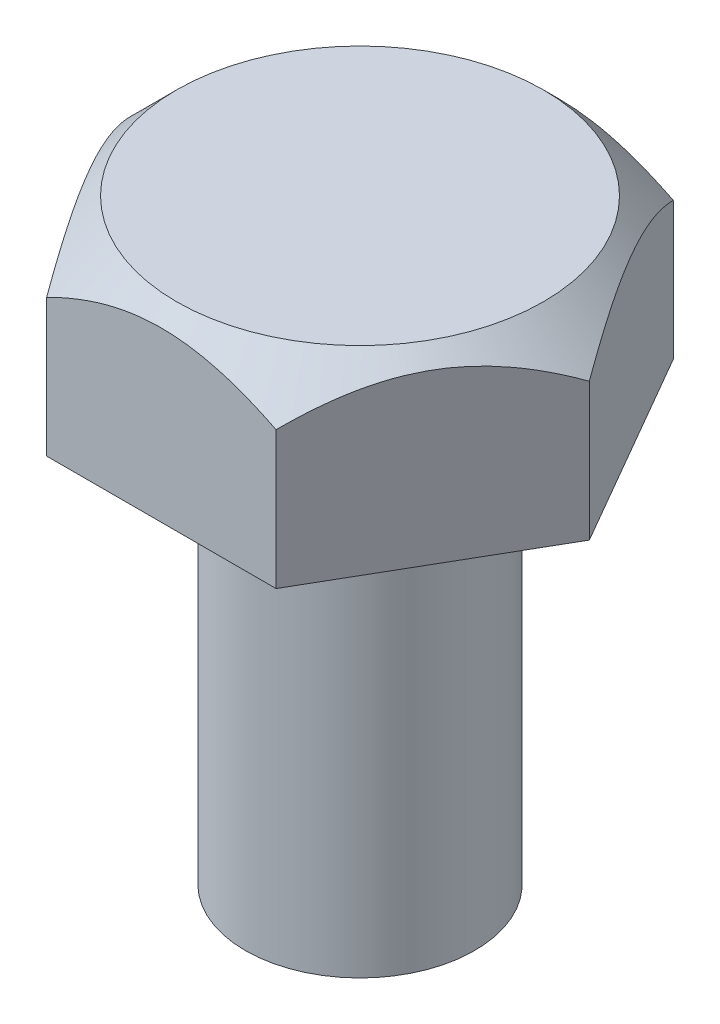
SolidWorks part; units mm, degrees
ref_plane "Front Plane" through (0, 0, 0) normal (0, 0, 1) x (1, 0, 0)
ref_plane "Top Plane" through (0, 0, 0) normal (0, 1, 0) x (1, 0, 0)
ref_plane "Right Plane" through (0, 0, 0) normal (1, 0, 0) x (0, 0, -1)
sketch "Sketch1" plane through (0, 0, 0) normal (0, 1, 0) x (1, 0, 0)
  circle A0 centre (0, 0) radius 2.5
  dimension "D1" = 5
extrude "Boss-Extrude1" add sketch "Sketch1" along normal blind 9
sketch "Sketch2" plane through (0, 9, 0) normal (0, 1, 0) x (1, 0, 0)
  line L1 (-2.5, -4.3301) -> (2.5, -4.3301)
  line L2 (2.5, -4.3301) -> (5, 0)
  line L3 (5, 0) -> (2.5, 4.3301)
  line L4 (2.5, 4.3301) -> (-2.5, 4.3301)
  line L5 (-2.5, 4.3301) -> (-5, 0)
  line L6 (-5, 0) -> (-2.5, -4.3301)
  circle A0 centre (0, 0) radius 4.3301 construction
  dimension "D1" = 10
extrude "Boss-Extrude2" add sketch "Sketch2" along normal blind 4
sketch "Sketch3" plane through (0, 0, 0) normal (0, 0, 1) x (1, 0, 0)
  line L0 (4, 13) -> (5, 12)
  line L1 (2.5, 13) -> (5, 13) construction
  line L2 (5, 13) -> (5, 9) construction
  line L3 (5, 12) -> (5, 13)
  line L4 (5, 13) -> (4, 13)
  line L5 (0, 9) -> (0, 15.1026) construction
  line L6 (-2.5, 9) -> (2.5, 9) construction
  dimension "D1" = 1
  dimension "D2" = 1
revolve "Cut-Revolve1" cut sketch "Sketch3" angle 360 about L5
